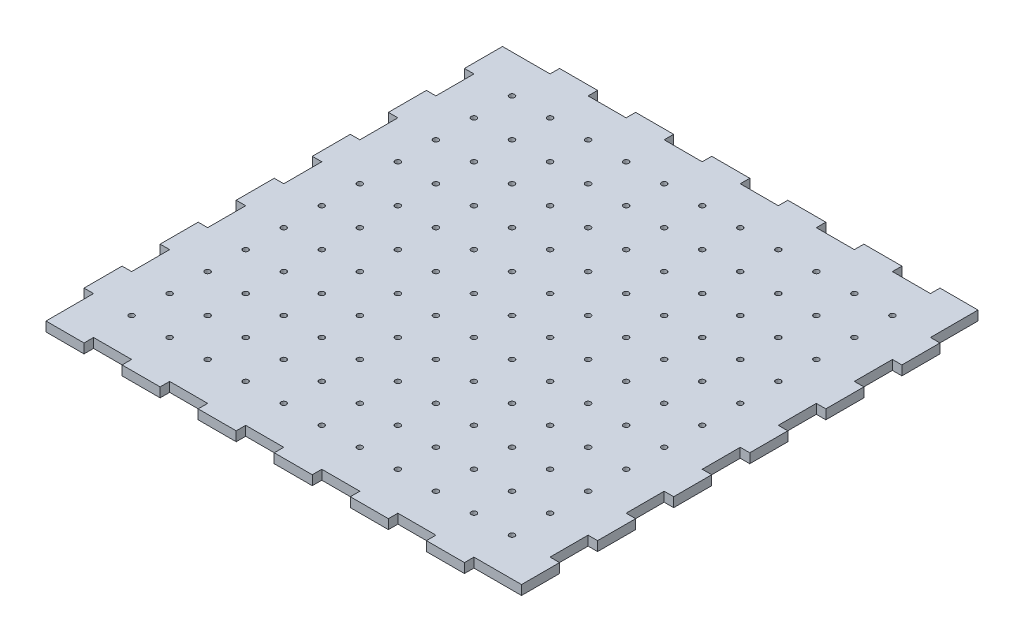
SolidWorks part; units mm, degrees
ref_plane "Front Plane" through (0, 0, 0) normal (0, 0, 1) x (1, 0, 0)
ref_plane "Top Plane" through (0, 0, 0) normal (0, 1, 0) x (1, 0, 0)
ref_plane "Right Plane" through (0, 0, 0) normal (1, 0, 0) x (0, 0, -1)
sketch "Sketch1" plane through (0, 0, 0) normal (0, 1, 0) x (1, 0, 0)
  line L0 (-65.2925, -101.6) -> (-39.8925, -101.6)
  line L1 (-97.0425, 152.4) -> (-97.0425, 127)
  line L2 (-97.0425, 203.2) -> (-97.0425, 177.8)
  line L3 (-90.6925, -107.95) -> (-65.2925, -107.95)
  line L4 (188.7075, 209.55) -> (214.1075, 209.55)
  line L5 (-90.6925, 177.8) -> (-90.6925, 152.4)
  line L6 (-97.0425, 203.2) -> (-65.2925, 203.2)
  line L7 (214.1075, 209.55) -> (214.1075, 177.8)
  line L8 (-65.2925, 209.55) -> (-65.2925, 203.2)
  line L9 (-39.8925, 209.55) -> (-39.8925, 203.2)
  line L10 (-14.4925, 209.55) -> (-14.4925, 203.2)
  line L11 (36.3075, 209.55) -> (36.3075, 203.2)
  line L12 (61.7075, 209.55) -> (61.7075, 203.2)
  line L13 (87.1075, 209.55) -> (87.1075, 203.2)
  line L14 (112.5075, 209.55) -> (112.5075, 203.2)
  line L15 (10.9075, 209.55) -> (10.9075, 203.2)
  line L16 (137.9075, 209.55) -> (137.9075, 203.2)
  line L17 (163.3075, 209.55) -> (163.3075, 203.2)
  line L18 (188.7075, 209.55) -> (188.7075, 203.2)
  line L19 (-97.0425, -76.2) -> (-90.6925, -76.2)
  line L20 (-97.0425, -50.8) -> (-90.6925, -50.8)
  line L21 (-97.0425, -25.4) -> (-90.6925, -25.4)
  line L22 (-97.0425, 0) -> (-90.6925, 0)
  line L23 (-97.0425, 25.4) -> (-90.6925, 25.4)
  line L24 (-97.0425, 50.8) -> (-90.6925, 50.8)
  line L25 (-97.0425, 76.2) -> (-90.6925, 76.2)
  line L26 (-97.0425, 101.6) -> (-90.6925, 101.6)
  line L27 (-97.0425, 127) -> (-90.6925, 127)
  line L28 (-97.0425, 152.4) -> (-90.6925, 152.4)
  line L29 (-97.0425, 177.8) -> (-90.6925, 177.8)
  line L30 (-39.8925, -107.95) -> (-14.4925, -107.95)
  line L31 (10.9075, -107.95) -> (36.3075, -107.95)
  line L32 (61.7075, -107.95) -> (87.1075, -107.95)
  line L33 (112.5075, -107.95) -> (137.9075, -107.95)
  line L34 (163.3075, -107.95) -> (188.7075, -107.95)
  line L35 (220.4575, -76.2) -> (220.4575, -101.6)
  line L36 (220.4575, -25.4) -> (220.4575, -50.8)
  line L37 (220.4575, 25.4) -> (220.4575, 0)
  line L38 (220.4575, 76.2) -> (220.4575, 50.8)
  line L39 (220.4575, 127) -> (220.4575, 101.6)
  line L40 (220.4575, 177.8) -> (220.4575, 152.4)
  line L41 (137.9075, 209.55) -> (163.3075, 209.55)
  line L42 (87.1075, 209.55) -> (112.5075, 209.55)
  line L43 (36.3075, 209.55) -> (61.7075, 209.55)
  line L44 (-14.4925, 209.55) -> (10.9075, 209.55)
  line L45 (-65.2925, 209.55) -> (-39.8925, 209.55)
  line L46 (-97.0425, 101.6) -> (-97.0425, 76.2)
  line L47 (-97.0425, 50.8) -> (-97.0425, 25.4)
  line L48 (-97.0425, 0) -> (-97.0425, -25.4)
  line L49 (-97.0425, -50.8) -> (-97.0425, -76.2)
  line L50 (-39.8925, 203.2) -> (-14.4925, 203.2)
  line L51 (10.9075, 203.2) -> (36.3075, 203.2)
  line L52 (61.7075, 203.2) -> (87.1075, 203.2)
  line L53 (112.5075, 203.2) -> (137.9075, 203.2)
  line L54 (163.3075, 203.2) -> (188.7075, 203.2)
  line L55 (214.1075, -76.2) -> (-90.6925, -76.2) construction
  line L56 (214.1075, -50.8) -> (-90.6925, -50.8) construction
  line L57 (-90.6925, -25.4) -> (214.1075, -25.4) construction
  line L58 (214.1075, 0) -> (-90.6925, 0) construction
  line L59 (-90.6925, 25.4) -> (214.1075, 25.4) construction
  line L60 (214.1075, 50.8) -> (-90.6925, 50.8) construction
  line L61 (-90.6925, 76.2) -> (214.1075, 76.2) construction
  line L62 (214.1075, 101.6) -> (-90.6925, 101.6) construction
  line L63 (-90.6925, 127) -> (214.1075, 127) construction
  line L64 (214.1075, 152.4) -> (-90.6925, 152.4) construction
  line L65 (-90.6925, 177.8) -> (214.1075, 177.8) construction
  line L66 (-90.6925, -76.2) -> (-90.6925, -107.95)
  line L67 (-90.6925, 127) -> (-90.6925, 101.6)
  line L68 (-90.6925, 76.2) -> (-90.6925, 50.8)
  line L69 (-90.6925, 25.4) -> (-90.6925, 0)
  line L70 (-90.6925, -25.4) -> (-90.6925, -50.8)
  line L71 (-14.4925, -101.6) -> (10.9075, -101.6)
  line L72 (36.3075, -101.6) -> (61.7075, -101.6)
  line L73 (87.1075, -101.6) -> (112.5075, -101.6)
  line L74 (137.9075, -101.6) -> (163.3075, -101.6)
  line L75 (188.7075, -101.6) -> (220.4575, -101.6)
  line L76 (214.1075, -50.8) -> (214.1075, -76.2)
  line L77 (214.1075, 0) -> (214.1075, -25.4)
  line L78 (214.1075, 50.8) -> (214.1075, 25.4)
  line L79 (214.1075, 76.2) -> (220.4575, 76.2)
  line L80 (214.1075, 101.6) -> (214.1075, 76.2)
  line L81 (214.1075, 152.4) -> (214.1075, 127)
  line L82 (214.1075, 177.8) -> (220.4575, 177.8)
  line L83 (214.1075, 152.4) -> (220.4575, 152.4)
  line L84 (214.1075, 127) -> (220.4575, 127)
  line L85 (214.1075, 101.6) -> (220.4575, 101.6)
  line L86 (214.1075, 50.8) -> (220.4575, 50.8)
  line L87 (214.1075, 25.4) -> (220.4575, 25.4)
  line L88 (214.1075, 0) -> (220.4575, 0)
  line L89 (214.1075, -25.4) -> (220.4575, -25.4)
  line L90 (214.1075, -50.8) -> (220.4575, -50.8)
  line L91 (214.1075, -76.2) -> (220.4575, -76.2)
  line L92 (188.7075, -101.6) -> (188.7075, -107.95)
  line L93 (163.3075, -101.6) -> (163.3075, -107.95)
  line L94 (137.9075, -101.6) -> (137.9075, -107.95)
  line L95 (112.5075, -101.6) -> (112.5075, -107.95)
  line L96 (87.1075, -101.6) -> (87.1075, -107.95)
  line L97 (61.7075, -101.6) -> (61.7075, -107.95)
  line L98 (36.3075, -101.6) -> (36.3075, -107.95)
  line L99 (10.9075, -101.6) -> (10.9075, -107.95)
  line L100 (-14.4925, -101.6) -> (-14.4925, -107.95)
  line L101 (-39.8925, -101.6) -> (-39.8925, -107.95)
  line L102 (-65.2925, -101.6) -> (-65.2925, -107.95)
  line L103 (-65.2925, 203.2) -> (-65.2925, -101.6) construction
  line L104 (-39.8925, 203.2) -> (-39.8925, -101.6) construction
  line L105 (-14.4925, 203.2) -> (-14.4925, -101.6) construction
  line L106 (10.9075, 203.2) -> (10.9075, -101.6) construction
  line L107 (36.3075, 203.2) -> (36.3075, -101.6) construction
  line L108 (61.7075, 203.2) -> (61.7075, -101.6) construction
  line L109 (87.1075, -101.6) -> (87.1075, 203.2) construction
  line L110 (112.5075, 203.2) -> (112.5075, -101.6) construction
  line L111 (137.9075, 203.2) -> (137.9075, -101.6) construction
  line L112 (163.3075, 203.2) -> (163.3075, -101.6) construction
  line L113 (188.7075, 203.2) -> (188.7075, -101.6) construction
  line L114 (-65.2925, -76.2) -> (-39.8925, -76.2) construction
  line L115 (-65.2925, -76.2) -> (-65.2925, -50.8) construction
  line L116 (-65.2925, -50.8) -> (-39.8925, -50.8) construction
  circle A0 centre (-65.2925, -76.2) radius 1.7907
  circle A1 centre (-39.8925, -76.2) radius 1.7907
  circle A2 centre (-14.4925, -76.2) radius 1.7907
  circle A3 centre (10.9075, -76.2) radius 1.7907
  circle A4 centre (36.3075, -76.2) radius 1.7907
  circle A5 centre (61.7075, -76.2) radius 1.7907
  circle A6 centre (87.1075, -76.2) radius 1.7907
  circle A7 centre (112.5075, -76.2) radius 1.7907
  circle A8 centre (137.9075, -76.2) radius 1.7907
  circle A9 centre (163.3075, -76.2) radius 1.7907
  circle A10 centre (188.7075, -76.2) radius 1.7907
  circle A11 centre (-65.2925, -50.8) radius 1.7907
  circle A12 centre (-65.2925, -25.4) radius 1.7907
  circle A13 centre (-65.2925, 0) radius 1.7907
  circle A14 centre (-65.2925, 25.4) radius 1.7907
  circle A15 centre (-65.2925, 50.8) radius 1.7907
  circle A16 centre (-65.2925, 76.2) radius 1.7907
  circle A17 centre (-65.2925, 101.6) radius 1.7907
  circle A18 centre (-65.2925, 127) radius 1.7907
  circle A19 centre (-65.2925, 152.4) radius 1.7907
  circle A20 centre (-65.2925, 177.8) radius 1.7907
  circle A21 centre (-39.8925, -50.8) radius 1.7907
  circle A22 centre (-14.4925, -50.8) radius 1.7907
  circle A23 centre (10.9075, -50.8) radius 1.7907
  circle A24 centre (36.3075, -50.8) radius 1.7907
  circle A25 centre (61.7075, -50.8) radius 1.7907
  circle A26 centre (87.1075, -50.8) radius 1.7907
  circle A27 centre (112.5075, -50.8) radius 1.7907
  circle A28 centre (137.9075, -50.8) radius 1.7907
  circle A29 centre (163.3075, -50.8) radius 1.7907
  circle A30 centre (188.7075, -50.8) radius 1.7907
  circle A31 centre (-39.8925, -25.4) radius 1.7907
  circle A32 centre (-14.4925, -25.4) radius 1.7907
  circle A33 centre (10.9075, -25.4) radius 1.7907
  circle A34 centre (36.3075, -25.4) radius 1.7907
  circle A35 centre (61.7075, -25.4) radius 1.7907
  circle A36 centre (87.1075, -25.4) radius 1.7907
  circle A37 centre (112.5075, -25.4) radius 1.7907
  circle A38 centre (137.9075, -25.4) radius 1.7907
  circle A39 centre (163.3075, -25.4) radius 1.7907
  circle A40 centre (188.7075, -25.4) radius 1.7907
  circle A41 centre (-39.8925, 0) radius 1.7907
  circle A42 centre (-14.4925, 0) radius 1.7907
  circle A43 centre (10.9075, 0) radius 1.7907
  circle A44 centre (36.3075, 0) radius 1.7907
  circle A45 centre (61.7075, 0) radius 1.7907
  circle A46 centre (87.1075, 0) radius 1.7907
  circle A47 centre (112.5075, 0) radius 1.7907
  circle A48 centre (137.9075, 0) radius 1.7907
  circle A49 centre (163.3075, 0) radius 1.7907
  circle A50 centre (188.7075, 0) radius 1.7907
  circle A51 centre (-39.8925, 25.4) radius 1.7907
  circle A52 centre (-14.4925, 25.4) radius 1.7907
  circle A53 centre (10.9075, 25.4) radius 1.7907
  circle A54 centre (36.3075, 25.4) radius 1.7907
  circle A55 centre (61.7075, 25.4) radius 1.7907
  circle A56 centre (87.1075, 25.4) radius 1.7907
  circle A57 centre (112.5075, 25.4) radius 1.7907
  circle A58 centre (137.9075, 25.4) radius 1.7907
  circle A59 centre (163.3075, 25.4) radius 1.7907
  circle A60 centre (188.7075, 25.4) radius 1.7907
  circle A61 centre (-39.8925, 50.8) radius 1.7907
  circle A62 centre (-14.4925, 50.8) radius 1.7907
  circle A63 centre (10.9075, 50.8) radius 1.7907
  circle A64 centre (36.3075, 50.8) radius 1.7907
  circle A65 centre (61.7075, 50.8) radius 1.7907
  circle A66 centre (87.1075, 50.8) radius 1.7907
  circle A67 centre (112.5075, 50.8) radius 1.7907
  circle A68 centre (137.9075, 50.8) radius 1.7907
  circle A69 centre (163.3075, 50.8) radius 1.7907
  circle A70 centre (188.7075, 50.8) radius 1.7907
  circle A71 centre (-39.8925, 76.2) radius 1.7907
  circle A72 centre (-14.4925, 76.2) radius 1.7907
  circle A73 centre (10.9075, 76.2) radius 1.7907
  circle A74 centre (36.3075, 76.2) radius 1.7907
  circle A75 centre (61.7075, 76.2) radius 1.7907
  circle A76 centre (87.1075, 76.2) radius 1.7907
  circle A77 centre (112.5075, 76.2) radius 1.7907
  circle A78 centre (137.9075, 76.2) radius 1.7907
  circle A79 centre (163.3075, 76.2) radius 1.7907
  circle A80 centre (188.7075, 76.2) radius 1.7907
  circle A81 centre (-39.8925, 101.6) radius 1.7907
  circle A82 centre (-14.4925, 101.6) radius 1.7907
  circle A83 centre (10.9075, 101.6) radius 1.7907
  circle A84 centre (36.3075, 101.6) radius 1.7907
  circle A85 centre (61.7075, 101.6) radius 1.7907
  circle A86 centre (87.1075, 101.6) radius 1.7907
  circle A87 centre (112.5075, 101.6) radius 1.7907
  circle A88 centre (137.9075, 101.6) radius 1.7907
  circle A89 centre (163.3075, 101.6) radius 1.7907
  circle A90 centre (188.7075, 101.6) radius 1.7907
  circle A91 centre (-39.8925, 127) radius 1.7907
  circle A92 centre (-14.4925, 127) radius 1.7907
  circle A93 centre (10.9075, 127) radius 1.7907
  circle A94 centre (36.3075, 127) radius 1.7907
  circle A95 centre (61.7075, 127) radius 1.7907
  circle A96 centre (87.1075, 127) radius 1.7907
  circle A97 centre (112.5075, 127) radius 1.7907
  circle A98 centre (137.9075, 127) radius 1.7907
  circle A99 centre (163.3075, 127) radius 1.7907
  circle A100 centre (188.7075, 127) radius 1.7907
  circle A101 centre (-39.8925, 152.4) radius 1.7907
  circle A102 centre (-14.4925, 152.4) radius 1.7907
  circle A103 centre (10.9075, 152.4) radius 1.7907
  circle A104 centre (36.3075, 152.4) radius 1.7907
  circle A105 centre (61.7075, 152.4) radius 1.7907
  circle A106 centre (87.1075, 152.4) radius 1.7907
  circle A107 centre (112.5075, 152.4) radius 1.7907
  circle A108 centre (137.9075, 152.4) radius 1.7907
  circle A109 centre (163.3075, 152.4) radius 1.7907
  circle A110 centre (188.7075, 152.4) radius 1.7907
  circle A111 centre (-39.8925, 177.8) radius 1.7907
  circle A112 centre (-14.4925, 177.8) radius 1.7907
  circle A113 centre (10.9075, 177.8) radius 1.7907
  circle A114 centre (36.3075, 177.8) radius 1.7907
  circle A115 centre (61.7075, 177.8) radius 1.7907
  circle A116 centre (87.1075, 177.8) radius 1.7907
  circle A117 centre (112.5075, 177.8) radius 1.7907
  circle A118 centre (137.9075, 177.8) radius 1.7907
  circle A119 centre (163.3075, 177.8) radius 1.7907
  circle A120 centre (188.7075, 177.8) radius 1.7907
  dimension "D5" = 3.5814
  dimension "D6" = 25.4
  dimension "D3" = 6.35
  dimension "D4" = 6.35
  dimension "D7" = 25.4
  dimension "D8" = 50.8
  dimension "D9" = 76.2
  dimension "D10" = 101.6
  dimension "D11" = 127
  dimension "D12" = 152.4
  dimension "D13" = 177.8
  dimension "D14" = 203.2
  dimension "D15" = 228.6
  dimension "D16" = 254
  dimension "D17" = 279.4
  dimension "D18" = 25.4
  dimension "D19" = 50.8
  dimension "D20" = 76.2
  dimension "D21" = 101.6
  dimension "D22" = 127
  dimension "D23" = 152.4
  dimension "D24" = 177.8
  dimension "D25" = 203.2
  dimension "D26" = 228.6
  dimension "D27" = 254
  dimension "D28" = 279.4
  dimension "D29" = 304.8
  dimension "D31" = 25.4
  dimension "D33" = 25.4
  dimension "D35" = 25.4
  dimension "D30" = 11
  dimension "D32" = 11
  dimension "D34" = 11
  dimension "D36" = 11
  dimension "D37" = 11
  dimension "D38" = 11
  dimension "D39" = 11
  dimension "D40" = 11
  dimension "D41" = 11
  dimension "D42" = 11
  dimension "D43" = 11
  dimension "D44" = 11
extrude "Boss-Extrude1" add sketch "Sketch1" along normal blind 6.35
